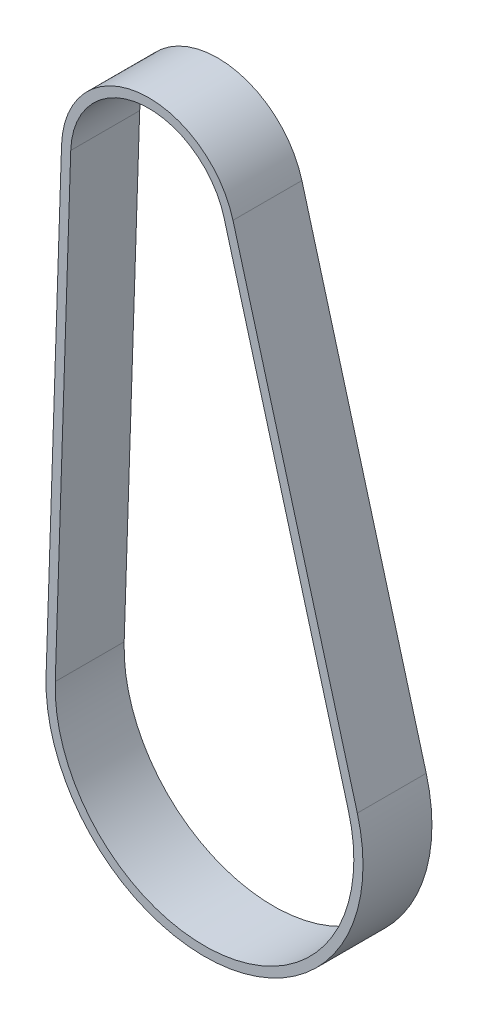
SolidWorks part; units mm, degrees
ref_plane "前视基准面" through (0, 0, 0) normal (0, 0, 1) x (1, 0, 0)
ref_plane "上视基准面" through (0, 0, 0) normal (0, 1, 0) x (1, 0, 0)
ref_plane "右视基准面" through (0, 0, 0) normal (1, 0, 0) x (0, 0, -1)
sketch "草图2" plane through (0, 0, 0) normal (0, 0, 1) x (1, 0, 0)
  line L0 (0, 0) -> (1, 0) construction
  line L1 (0, 0) -> (0, 1) construction
  line L2 (-52.1292, 51.6491) -> (-45.3822, 255.2578)
  line L3 (25.3044, 263.6295) -> (79.4263, 67.2298)
  arc A0 (79.4263, 67.2298) -> (-52.1292, 51.6491) centre (14.834, 49.4301) cw
  arc A1 (-45.3822, 255.2578) -> (25.3044, 263.6295) centre (-9.402, 254.0655) cw
extrude "拉伸-薄壁2" add sketch "草图2" along normal mid plane 30 thin thin type two direction wall 2 second wall 2
